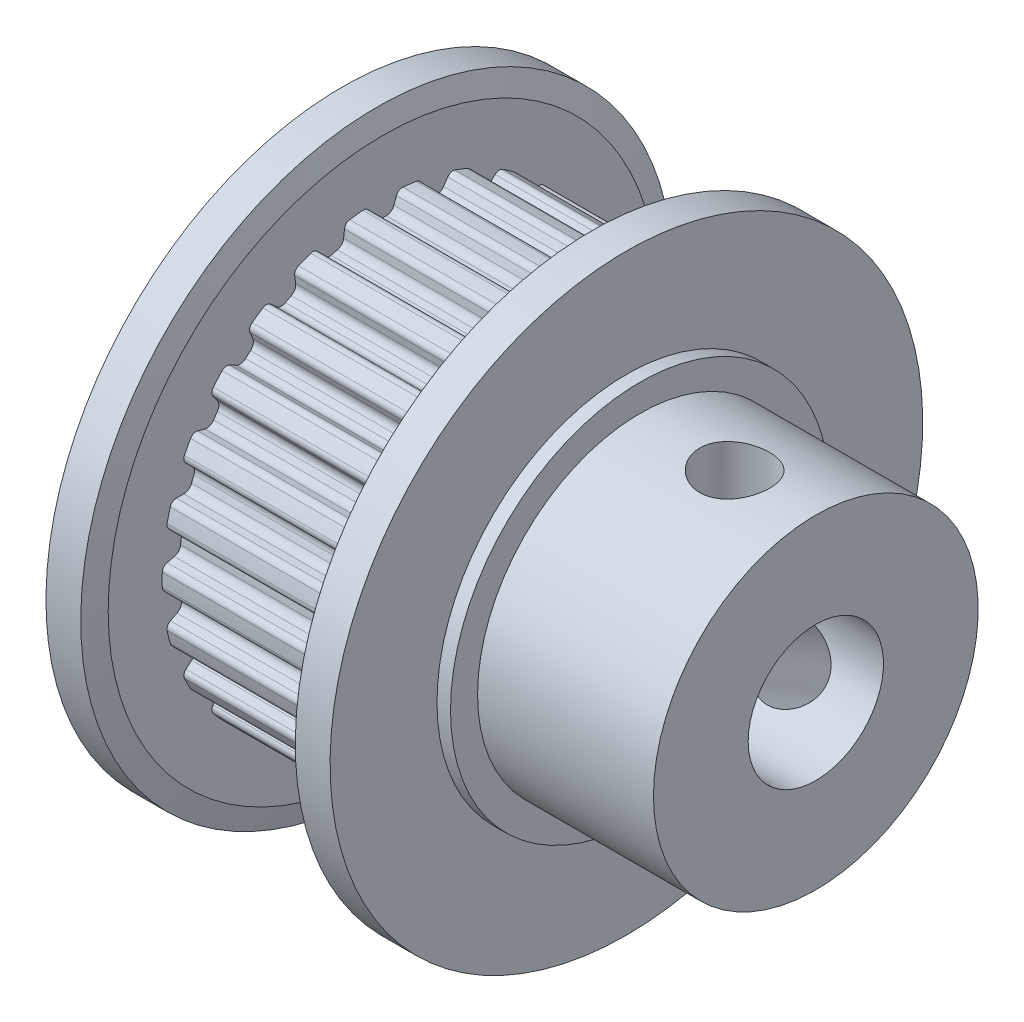
SolidWorks part; units mm, degrees
ref_plane "前视基准面" through (0, 0, 0) normal (0, 0, 1) x (1, 0, 0)
ref_plane "上视基准面" through (0, 0, 0) normal (0, 1, 0) x (1, 0, 0)
ref_plane "右视基准面" through (0, 0, 0) normal (1, 0, 0) x (0, 0, -1)
sketch "草图1" plane through (0, 0, 0) normal (0, 0, 1) x (1, 0, 0)
  line L0 (-5.75, 7) -> (-3.75, 7)
  line L1 (-3.75, 7) -> (-3.75, 8.155)
  line L2 (-3.75, 8.155) -> (3.75, 8.155)
  line L3 (0, 0) -> (0, 8.155) construction
  line L4 (-5.75, 7) -> (-5.75, 0)
  line L5 (5.75, 7) -> (5.75, 0)
  line L6 (3.75, 7) -> (3.75, 8.155)
  line L7 (5.75, 7) -> (3.75, 7)
  line L8 (-5.75, 0) -> (5.75, 0)
  dimension "D1" = 7
  dimension "D2" = 8.155
  dimension "D3" = 7.5
  dimension "D4" = 11.5
revolve "旋转1" add sketch "草图1" angle 360 about L8
sketch "草图3" plane through (0, 0, 0) normal (1, 0, 0) x (0, 0, -1)
  line L0 (0, 0) -> (0, 8.155) construction
  line L1 (-0.335, 7.5075) -> (-0.5636, 8.1355)
  line L2 (0.5636, 8.1355) -> (0.335, 7.5075)
  arc A0 (0.5636, 8.1355) -> (-0.5636, 8.1355) centre (0, 0) ccw
  circle A1 centre (0, 0) radius 8.155 construction
  arc A2 (0.335, 7.5075) -> (-0.335, 7.5075) centre (0, 0) ccw
  dimension "D4" = 0.64
  dimension "D1" = 0.67
  dimension "D2" = 20
  dimension "D3" = 20
extrude "切除-拉伸3" cut sketch "草图3" against normal mid plane 7.5
fillet "圆角3" radius 0.23 2 edges at (0, 8.1355, -0.5636) (0, 8.1355, 0.5636)
fillet "圆角4" radius 0.3 2 edges at (0, 7.5075, -0.335) (0, 7.5075, 0.335)
pattern_circular "阵列(圆周)2" count 26 over 360 about axis through (0, 0, 0) along (1, 0, 0) of "圆角3", "切除-拉伸3", "圆角4"
sketch "草图4" plane through (0, 0, 0) normal (0, 0, 1) x (1, 0, 0)
  line L0 (-5.25, 10.95) -> (-5.25, 7)
  line L1 (-3.75, 7) -> (-5.75, 7) construction
  line L2 (5.25, 10.95) -> (5.25, 7)
  line L3 (-5.25, 10.95) -> (-3.9644, 10.95)
  line L4 (-3.9644, 10.95) -> (-3.75, 10.15)
  line L5 (-3.75, 10.15) -> (-3.75, 7)
  line L6 (-3.75, 7) -> (-5.25, 7)
  line L7 (-3.75, 8.155) -> (-3.75, -8.155) construction
  line L9 (0, 0) -> (0, 9.52) construction
  line L11 (-5.75, 0) -> (5.75, 0) construction
  line L12 (-5.75, 7) -> (-5.75, -7) construction
  line L13 (5.75, -7) -> (5.75, 7) construction
  line L14 (3.75, 10.15) -> (3.75, 7)
  line L15 (3.75, 7) -> (5.25, 7)
  line L17 (3.9644, 10.95) -> (3.75, 10.15)
  line L18 (5.25, 10.95) -> (3.9644, 10.95)
  dimension "D1" = 1.5
  dimension "D2" = 15
  dimension "D3" = 10.95
  dimension "D4" = 0.8
revolve "旋转2" add sketch "草图4" angle 360 about L11
sketch "草图5" plane through (0, 0, 0) normal (0, 0, 1) x (1, 0, 0)
  line L0 (5.75, -7) -> (5.75, 7) construction
  line L1 (5.75, 0) -> (12.25, 0)
  line L2 (5.75, 0) -> (5.75, 6)
  line L3 (5.75, 6) -> (12.25, 6)
  line L4 (12.25, 0) -> (12.25, 6)
  dimension "D1" = 6
  dimension "D2" = 6.5
revolve "旋转3" add sketch "草图5" angle 360 about L1
sketch "草图37" [suppressed] plane through (0, 0, 0) normal (0, 0, 1) x (1, 0, 0)
  line L0 (-5, 0) -> (5, 0) construction
  line L1 (-5, 8.95) -> (-3, 8.95)
  line L2 (-5, 8.95) -> (-5, 5.5)
  line L3 (-5, 5.5) -> (-3, 5.5)
  line L4 (-3, 8.95) -> (-3, 5.5)
  line L5 (-5, 5.5) -> (-5, -5.5) construction
  line L6 (5, -5.5) -> (5, 5.5) construction
  line L7 (0, 0) -> (0, 7.8967) construction
  line L8 (3, 8.95) -> (3, 5.5)
  line L9 (5, 5.5) -> (3, 5.5)
  line L10 (5, 8.95) -> (3, 8.95)
  line L11 (5, 8.95) -> (5, 5.5)
  dimension "D1" = 3.75
  dimension "D2" = 7
  dimension "D3" = 10.95
  dimension "D4" = 2
revolve "切除-旋转5" [suppressed] cut sketch "草图37" angle 360 about L0
sketch "草图6" [suppressed] plane through (0, 0, 0) normal (0, 0, 1) x (1, 0, 0)
  line L0 (-4.5, 5.95) -> (-4.5, 3)
  line L1 (-3, 3) -> (-5, 3) construction
  line L3 (-4.5, 5.95) -> (-3.2144, 5.95)
  line L4 (-3.2144, 5.95) -> (-3, 5.15)
  line L5 (-3, 5.15) -> (-3, 3)
  line L6 (-3, 3) -> (-4.5, 3)
  line L8 (3, 0) -> (3, 5.15)
  line L9 (3, 5.15) -> (3.2278, 6)
  line L10 (3.2278, 6) -> (11.5, 6)
  line L11 (11.5, 6) -> (11.5, 0)
  line L12 (11.5, 0) -> (3, 0)
  line L14 (-5, 0) -> (5, 0) construction
  line L15 (-5, 3) -> (-5, -3) construction
  line L16 (5, -3) -> (5, 3) construction
  dimension "D1" = 1.5
  dimension "D2" = 15
  dimension "D3" = 0.8
  dimension "D4" = 10.95
  dimension "D5" = 6
  dimension "D6" = 15
  dimension "D7" = 18
  dimension "D8" = 3.75
revolve "旋转4" [suppressed] add sketch "草图6" angle 360 about L14
sketch "草图7" plane through (-5.75, 0, 0) normal (-1, 0, 0) x (0, 0, 1)
  circle A0 centre (0, 0) radius 2.5
  dimension "D1" = 5
extrude "切除-拉伸4" cut sketch "草图7" against normal through all
sketch "草图31" plane through (0, 0, 0) normal (0, 1, 0) x (1, 0, 0)
  circle A0 centre (9.25, 0) radius 1.29
  dimension "D2" = 2.58
  dimension "D1" = 9.25
extrude "切除-拉伸21" cut sketch "草图31" along normal through all
cosmetic thread "装饰螺纹线9" parameters "D2"=3
sketch "草图32" plane through (0, 0, 0) normal (0, 1, 0) x (1, 0, 0)
  line L0 (0, 0) -> (-5.75, 0) construction
  line L1 (-5.75, 7) -> (-5.75, -7) construction
ref_plane "基准面5" through (0, 0, 0) normal (0, -0.5, -0.866) x (1, 0, 0)
sketch "草图33" plane through (0, 0, 0) normal (0, -0.5, -0.866) x (1, 0, 0)
  circle A0 centre (9.25, 0) radius 1.29
  dimension "D2" = 2.58
  dimension "D1" = 9.25
extrude "切除-拉伸22" cut sketch "草图33" along normal through all
cosmetic thread "装饰螺纹线10" parameters "D2"=3
sketch "草图16" [suppressed] plane through (-5, 0, 0) normal (-1, 0, 0) x (0, 0, 1)
  line L0 (-1.5, 0) -> (-1.5, 2.9)
  line L1 (-1.5, 2.9) -> (1.5, 2.9)
  line L2 (1.5, 2.9) -> (1.5, 0)
  arc A0 (-1.5, 0) -> (1.5, 0) centre (0, 0) ccw
  dimension "D2" = 2.5
  dimension "D1" = 3
  dimension "D3" = 3.9
extrude "切除-拉伸10" [suppressed] cut sketch "草图16" against normal through all
sketch "草图27" [suppressed] plane through (11.5, 0, 0) normal (1, 0, 0) x (0, 0, -1)
  circle A0 centre (0, 0) radius 5
  dimension "D1" = 10
extrude "切除-拉伸19" [suppressed] cut sketch "草图27" against normal blind 5
sketch "草图29" [suppressed] plane through (0, 0, 0) normal (0, 0, 1) x (1, 0, 0)
  line L0 (-5, 4.5) -> (-2, 4.5)
  line L1 (-5, 5.5) -> (-5, -5.5) construction
  line L2 (-2, 4.5) -> (-2, 1.5)
  line L3 (-2, 1.5) -> (2, 1.5)
  line L4 (2, 1.5) -> (2, 5)
  line L5 (2, 5) -> (5, 5)
  line L6 (5, -5.5) -> (5, 5.5) construction
  line L7 (5, 5) -> (5, 0)
  line L8 (5, 0) -> (-5, 0)
  line L9 (-5, 0) -> (-5, 4.5)
  dimension "D1" = 4.5
  dimension "D2" = 3
  dimension "D3" = 3
  dimension "D4" = 5
  dimension "D5" = 2.5
revolve "切除-旋转1" [suppressed] cut sketch "草图29" angle 360 about L8
sketch "草图38" [suppressed] plane through (0, 0, 0) normal (0, 0, 1) x (1, 0, 0)
  line L0 (-5, 5.5) -> (-5, -5.5) construction
  line L1 (-5, 0) -> (0, 0)
  line L2 (-5, 0) -> (-5, 5)
  line L3 (-5, 5) -> (0, 5)
  line L4 (0, 0) -> (0, 5)
  dimension "D1" = 5
  dimension "D2" = 5
revolve "切除-旋转6" [suppressed] cut sketch "草图38" angle 360 about L1
sketch "草图36" [suppressed] plane through (0, 0, 0) normal (0, 0, 1) x (1, 0, 0)
  line L0 (0, 0) -> (-5, 0) construction
  line L1 (-3, 4.275) -> (-5, 4.275)
  line L2 (-3, 4.275) -> (-3, 5.95)
  line L3 (-3, 5.95) -> (-5, 5.95)
  line L4 (-5, 4.275) -> (-5, 5.95)
  line L5 (-5, 3) -> (-5, -3) construction
  dimension "D1" = 8.155
  dimension "D2" = 10.95
  dimension "D3" = 3.75
  dimension "D4" = 2
revolve "切除-旋转4" [suppressed] cut sketch "草图36" angle 360 about L0
sketch "草图35" [suppressed] plane through (0, 0, 0) normal (0, 0, 1) x (1, 0, 0)
  line L0 (-5, 0) -> (0, 0) construction
  line L1 (3, 4.275) -> (5, 4.275)
  line L2 (3, 4.275) -> (3, 5.95)
  line L3 (3, 5.95) -> (5, 5.95)
  line L4 (5, 4.275) -> (5, 5.95)
  line L5 (-5, 3) -> (-5, -3) construction
  dimension "D1" = 8.155
  dimension "D2" = 10.95
  dimension "D3" = 2
  dimension "D4" = 3.75
revolve "切除-旋转3" [suppressed] cut sketch "草图35" angle 360 about L0
sketch "草图39" [suppressed] plane through (0, 0, 0) normal (0, 0, 1) x (1, 0, 0)
  line L0 (-1000, 0) -> (49000, 0) construction
  line L1 (4.5, -8.95) -> (4.5, 8.95) construction
  line L2 (-4.5, 8.95) -> (4.5, 8.95)
  line L3 (-4.5, 8.95) -> (-4.5, 8)
  line L4 (-4.5, 8) -> (4.5, 8)
  line L5 (4.5, 8.95) -> (4.5, 8)
  dimension "D1" = 8
revolve "切除-旋转7" [suppressed] cut sketch "草图39" angle 360 about L0
sketch "草图40" [suppressed] plane through (0, 0, 0) normal (0, 0, 1) x (1, 0, 0)
  line L0 (11.5, 4.29) -> (5.5, 4.29)
  line L1 (11.5, -4.5) -> (11.5, 4.5) construction
  line L2 (5.5, 4.29) -> (4.7249, 3)
  line L3 (4.7249, 3) -> (11.5, 3)
  line L4 (11.5, 3) -> (11.5, 4.29)
  dimension "D1" = 59
  dimension "D2" = 1.29
  dimension "D3" = 6
  dimension "D4" = 3
revolve "切除-旋转8" [suppressed] cut sketch "草图40" angle 360 about L3
cosmetic thread "装饰螺纹线11" [suppressed] parameters "D2"=3
pattern_circular "阵列(圆周)3" [suppressed] count 4 over 360
sketch "草图41" [suppressed] plane through (0, 0, 0) normal (0, 0, 1) x (1, 0, 0)
  line L0 (11.5, 4.29) -> (5.5, 4.29)
  line L1 (11.5, -4.5) -> (11.5, 4.5) construction
  line L2 (5.5, 4.29) -> (4.7249, 3)
  line L3 (4.7249, 3) -> (11.5, 3)
  line L4 (11.5, 3) -> (11.5, 4.29)
  dimension "D1" = 59
  dimension "D2" = 3
  dimension "D3" = 1.29
  dimension "D4" = 6
revolve "切除-旋转9" [suppressed] cut sketch "草图41" angle 360 about L3
cosmetic thread "装饰螺纹线12" [suppressed] parameters "D2"=3
pattern_circular "阵列(圆周)4" [suppressed] count 3 over 360
sketch "草图42" [suppressed] plane through (0, 0, 0) normal (0, 0, 1) x (1, 0, 0)
  line L0 (11.5, 4.29) -> (5.5, 4.29)
  line L1 (11.5, -4.5) -> (11.5, 4.5) construction
  line L2 (5.5, 4.29) -> (4.7249, 3)
  line L3 (4.7249, 3) -> (11.5, 3)
  line L4 (11.5, 3) -> (11.5, 4.29)
  dimension "D1" = 59
  dimension "D2" = 3
  dimension "D3" = 1.29
  dimension "D4" = 6
revolve "切除-旋转10" [suppressed] cut sketch "草图42" angle 360 about L3
cosmetic thread "装饰螺纹线13" [suppressed] parameters "D2"=3
pattern_circular "阵列(圆周)5" [suppressed] count 6 over 360
sketch "草图43" [suppressed] plane through (0, 0, 0) normal (0, 0, 1) x (1, 0, 0)
  line L0 (11.5, -4.55) -> (11.5, 4.55) construction
  line L1 (11.5, 3) -> (-5, 3)
  line L2 (11.5, 3) -> (11.5, 4.5)
  line L3 (11.5, 4.5) -> (-5, 4.5)
  line L4 (-5, 3) -> (-5, 4.5)
  line L5 (-5, 5.5) -> (-5, -5.5) construction
  dimension "D1" = 3
  dimension "D2" = 1.5
revolve "切除-旋转12" [suppressed] cut sketch "草图43" angle 360 about L1
pattern_circular "阵列(圆周)6" [suppressed] count 4 over 360
sketch "草图44" [suppressed] plane through (0, 0, 0) normal (0, 0, 1) x (1, 0, 0)
  line L0 (11.5, -4.55) -> (11.5, 4.55) construction
  line L1 (11.5, 3) -> (-5, 3)
  line L2 (11.5, 3) -> (11.5, 4.5)
  line L3 (11.5, 4.5) -> (-5, 4.5)
  line L4 (-5, 3) -> (-5, 4.5)
  line L5 (-5, 5.5) -> (-5, -5.5) construction
  dimension "D1" = 3
  dimension "D2" = 1.5
revolve "切除-旋转13" [suppressed] cut sketch "草图44" angle 360 about L1
pattern_circular "阵列(圆周)7" [suppressed] count 3 over 360
sketch "草图45" [suppressed] plane through (0, 0, 0) normal (0, 0, 1) x (1, 0, 0)
  line L0 (11.5, -4.55) -> (11.5, 4.55) construction
  line L1 (11.5, 3) -> (-5, 3)
  line L2 (11.5, 3) -> (11.5, 4.45)
  line L3 (11.5, 4.45) -> (-5, 4.45)
  line L4 (-5, 3) -> (-5, 4.45)
  line L5 (-5, 5.5) -> (-5, -5.5) construction
  dimension "D1" = 3
  dimension "D2" = 1.45
revolve "切除-旋转14" [suppressed] cut sketch "草图45" angle 360 about L1
pattern_circular "阵列(圆周)12" [suppressed] count 6 over 360
sketch "草图46" [suppressed] plane through (0, 0, 0) normal (0, 0, 1) x (1, 0, 0)
  line L0 (-5, 4.65) -> (8, 4.65)
  line L1 (-5, 5.5) -> (-5, -5.5) construction
  line L2 (8, 4.65) -> (8, 6.25)
  line L3 (8, 6.25) -> (11.5, 6.25)
  line L4 (11.5, -4.55) -> (11.5, 4.55) construction
  line L5 (11.5, 6.25) -> (11.5, 3)
  line L6 (11.5, 3) -> (-5, 3)
  line L7 (-5, 3) -> (-5, 4.65)
  dimension "D1" = 3
  dimension "D2" = 1.65
  dimension "D3" = 3.25
  dimension "D4" = 3.5
revolve "切除-旋转15" [suppressed] cut sketch "草图46" angle 360 about L6
pattern_circular "阵列(圆周)13" [suppressed] count 4 over 360
sketch "草图47" [suppressed] plane through (0, 0, 0) normal (0, 0, 1) x (1, 0, 0)
  line L0 (-5, 4.65) -> (8, 4.65)
  line L1 (-5, 5.5) -> (-5, -5.5) construction
  line L2 (8, 4.65) -> (8, 6.25)
  line L3 (8, 6.25) -> (11.5, 6.25)
  line L4 (11.5, -4.55) -> (11.5, 4.55) construction
  line L5 (11.5, 6.25) -> (11.5, 3)
  line L6 (11.5, 3) -> (-5, 3)
  line L7 (-5, 3) -> (-5, 4.65)
  dimension "D1" = 3
  dimension "D2" = 1.65
  dimension "D3" = 3.25
  dimension "D4" = 3.5
revolve "切除-旋转16" [suppressed] cut sketch "草图47" angle 360 about L6
pattern_circular "阵列(圆周)14" [suppressed] count 3 over 360
sketch "草图48" [suppressed] plane through (0, 0, 0) normal (0, 0, 1) x (1, 0, 0)
  line L0 (-5, 4.65) -> (8, 4.65)
  line L1 (-5, 5.5) -> (-5, -5.5) construction
  line L2 (8, 4.65) -> (8, 6.25)
  line L3 (8, 6.25) -> (11.5, 6.25)
  line L4 (11.5, -4.55) -> (11.5, 4.55) construction
  line L5 (11.5, 6.25) -> (11.5, 3)
  line L6 (11.5, 3) -> (-5, 3)
  line L7 (-5, 3) -> (-5, 4.65)
  dimension "D1" = 3
  dimension "D2" = 1.65
  dimension "D3" = 3.25
  dimension "D4" = 3.5
revolve "切除-旋转17" [suppressed] cut sketch "草图48" angle 360 about L6
pattern_circular "阵列(圆周)15" [suppressed] count 6 over 360
